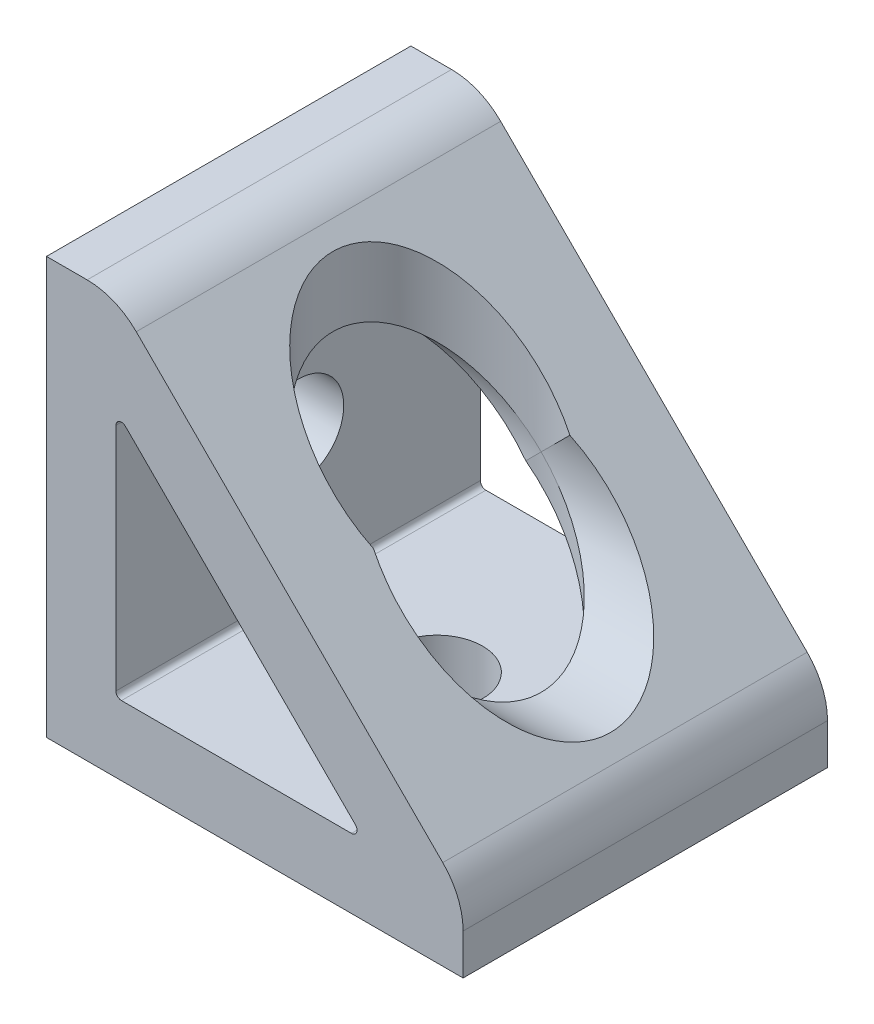
SolidWorks part; units mm, degrees
material "6105-T5 Aluminum"
ref_plane "Front Plane" through (0, 0, 0) normal (0, 0, 1) x (1, 0, 0)
ref_plane "Top Plane" through (0, 0, 0) normal (0, 1, 0) x (1, 0, 0)
ref_plane "Right Plane" through (0, 0, 0) normal (1, 0, 0) x (0, 0, -1)
sketch "Sketch2" plane through (0, 0, 0) normal (0, 0, 1) x (1, 0, 0)
  line L0 (0, 38.1) -> (0, 0)
  line L1 (0, 0) -> (38.1, 0)
  line L2 (38.1, 0) -> (38.1, 3.7197)
  line L3 (8.2099, 36.2401) -> (36.2401, 8.2099)
  line L4 (3.7197, 38.1) -> (0, 38.1)
  line L5 (6.35, 27.8933) -> (6.35, 6.858)
  line L6 (6.858, 6.35) -> (27.8933, 6.35)
  line L7 (7.2172, 28.2525) -> (28.2525, 7.2172)
  line L8 (3.7197, 31.75) -> (31.75, 3.7197) construction
  arc A0 (38.1, 3.7197) -> (36.2401, 8.2099) centre (31.75, 3.7197) ccw
  arc A1 (3.7197, 38.1) -> (8.2099, 36.2401) centre (3.7197, 31.75) cw
  arc A2 (6.35, 6.858) -> (6.858, 6.35) centre (6.858, 6.858) ccw
  arc A3 (27.8933, 6.35) -> (28.2525, 7.2172) centre (27.8933, 6.858) ccw
  arc A4 (7.2172, 28.2525) -> (6.35, 27.8933) centre (6.858, 27.8933) ccw
  point P7 (38.1, 6.35)
  point P16 (6.35, 38.1)
  dimension "D1" = 6.35
  dimension "D7" = 0.508
  dimension "D5" = 6.35
  dimension "D9" = 0.508
  dimension "D2" = 38.1
  dimension "D3" = 38.1
  dimension "D4" = 6.35
  dimension "D6" = 6.35
  dimension "D8" = 6.35
extrude "Boss-Extrude2" add sketch "Sketch2" along normal mid plane 33.3248
sketch "Sketch3" plane through (0, 0, 0) normal (-1, 0, 0) x (0, 0, 1)
  line L2 (0, 0) -> (0, 19.05) construction
  circle A0 centre (0, 19.05) radius 4.1694
  dimension "D1" = 8.3388
  dimension "D2" = 19.05
extrude "Cut-Extrude1" cut sketch "Sketch3" against normal up to next
sketch "Sketch4" plane through (6.35, 0, 0) normal (1, 0, 0) x (0, 0, -1)
  circle A0 centre (0, 19.05) radius 9.525
  dimension "D1" = 19.05
extrude "Cut-Extrude2" cut sketch "Sketch4" along normal blind 36.068
sketch "Sketch5" plane through (0, 0, 0) normal (0, -1, 0) x (1, 0, 0)
  line L0 (0, 16.6624) -> (0, -16.6624) construction
  line L2 (19.05, 0) -> (0, 0) construction
  circle A0 centre (19.05, 0) radius 4.1656
  dimension "D3" = 8.3312
  dimension "D1" = 19.05
extrude "Cut-Extrude3" cut sketch "Sketch5" against normal up to next
sketch "Sketch6" plane through (0, 6.35, 0) normal (0, 1, 0) x (1, 0, 0)
  line L0 (19.05, 0) -> (0, 0) construction
  line L1 (0, -16.6624) -> (0, 16.6624) construction
  circle A0 centre (19.05, 0) radius 9.525
  dimension "D1" = 19.05
extrude "Cut-Extrude4" cut sketch "Sketch6" along normal blind 36.068
